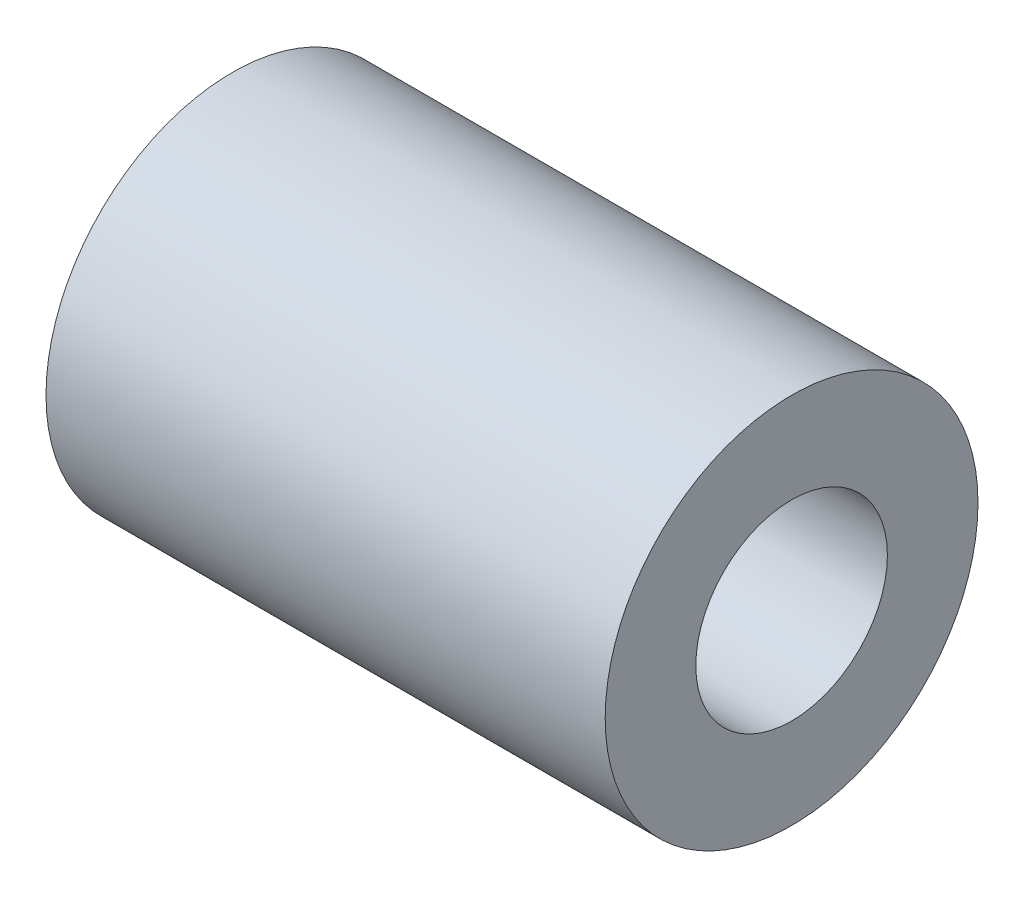
SolidWorks part; units mm, degrees
material "6061-T6 (SS)"
ref_plane "Front Plane" through (0, 0, 0) normal (0, 0, 1) x (1, 0, 0)
ref_plane "Top Plane" through (0, 0, 0) normal (0, 1, 0) x (1, 0, 0)
ref_plane "Right Plane" through (0, 0, 0) normal (1, 0, 0) x (0, 0, -1)
sketch "Sketch1" plane through (0, 0, 0) normal (1, 0, 0) x (0, 0, -1)
  circle A0 centre (0, 0) radius 6.35
  circle A1 centre (0, 0) radius 3.2639
  dimension "D1" = 12.7
  dimension "D2" = 6.5278
extrude "Boss-Extrude1" add sketch "Sketch1" along normal blind 19.05
